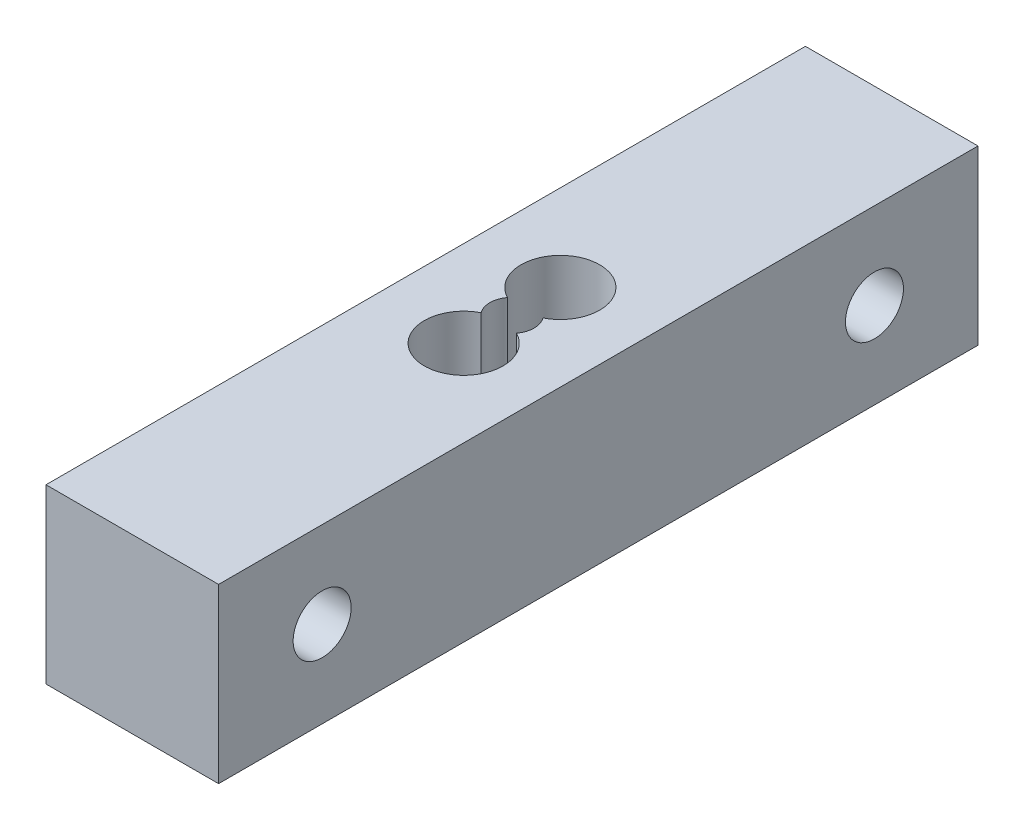
SolidWorks part; units mm, degrees
ref_plane "Plan de face" through (0, 0, 0) normal (0, 0, 1) x (1, 0, 0)
ref_plane "Plan de dessus" through (0, 0, 0) normal (0, 1, 0) x (1, 0, 0)
ref_plane "Plan de droite" through (0, 0, 0) normal (1, 0, 0) x (0, 0, -1)
sketch "Esquisse1" plane through (0, 0, 0) normal (0, 0, 1) x (1, 0, 0)
  line L1 (-6.25, 6.25) -> (6.25, 6.25)
  line L2 (-6.25, 6.25) -> (-6.25, -6.25)
  line L3 (-6.25, -6.25) -> (6.25, -6.25)
  line L4 (6.25, 6.25) -> (6.25, -6.25)
  line L5 (-6.25, 6.25) -> (6.25, -6.25) construction
  line L6 (-6.25, -6.25) -> (6.25, 6.25) construction
  point P0 (0, 0)
  dimension "D1" = 12.5
  dimension "D2" = 12.5
extrude "Boss.-Extru.1" add sketch "Esquisse1" along normal mid plane 55
sketch "Esquisse2" plane through (0, 0, 0) normal (0, 1, 0) x (1, 0, 0)
  line L0 (0, 27.5) -> (0, -27.5) construction
  line L1 (6.25, 27.5) -> (-6.25, 27.5) construction
  line L2 (6.25, -27.5) -> (-6.25, -27.5) construction
  line L3 (0, 0) -> (5.461, 0) construction
  circle A0 centre (0, 3.5) radius 2.85
  circle A1 centre (0, -3.5) radius 2.85
  point P13 (0, 0)
  dimension "D1" = 5.7
  dimension "D2" = 7
extrude "Enlèv. mat.-Extru.1" cut sketch "Esquisse2" against normal through all and the other way through all
sketch "Esquisse3" plane through (0, 0, 0) normal (0, 1, 0) x (1, 0, 0)
  circle A0 centre (0, 0) radius 1.6
  dimension "D1" = 3.2
extrude "Enlèv. mat.-Extru.2" cut sketch "Esquisse3" against normal through all and the other way through all
sketch "Esquisse4" plane through (0, 0, 0) normal (1, 0, 0) x (0, 0, -1)
  line L0 (-27.5, 0) -> (27.5, 0) construction
  line L1 (-27.5, -6.25) -> (-27.5, 6.25) construction
  line L2 (27.5, -6.25) -> (27.5, 6.25) construction
  line L3 (0, 0) -> (0, 4.6009) construction
  circle A0 centre (-20, 0) radius 2.1
  circle A1 centre (20, 0) radius 2.1
  point P13 (0, 0)
  dimension "D1" = 4.2
  dimension "D2" = 40
extrude "Enlèv. mat.-Extru.3" cut sketch "Esquisse4" against normal through all and the other way through all
